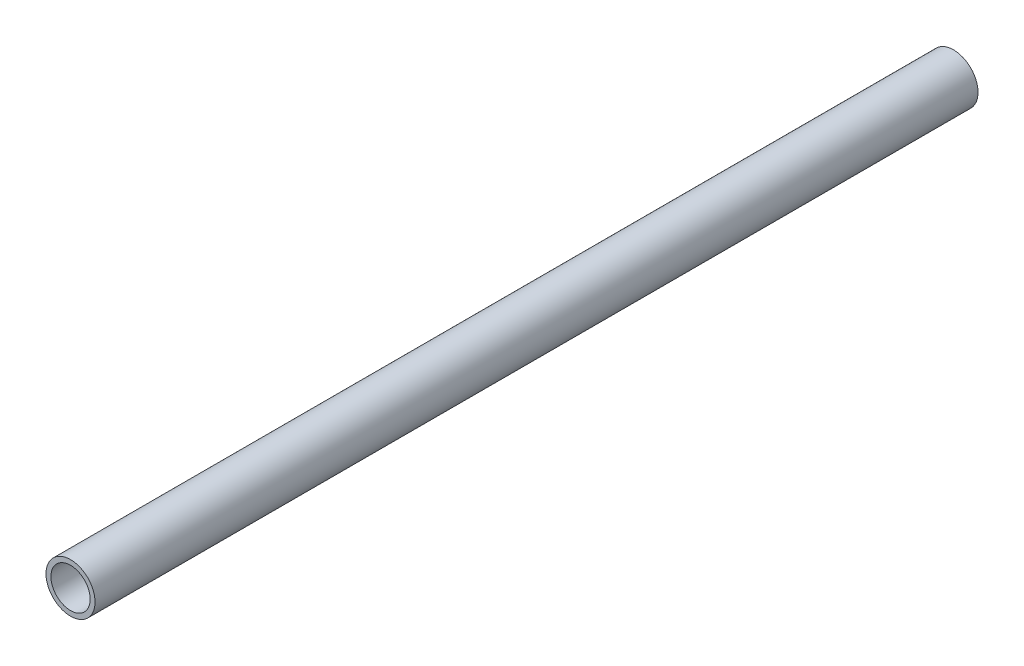
SolidWorks part; units mm, degrees
material "Thornel Mat VMA"
ref_plane "前视基准面" through (0, 0, 0) normal (0, 0, 1) x (1, 0, 0)
ref_plane "上视基准面" through (0, 0, 0) normal (0, 1, 0) x (1, 0, 0)
ref_plane "右视基准面" through (0, 0, 0) normal (1, 0, 0) x (0, 0, -1)
sketch "草图1" plane through (0, 0, 0) normal (0, 0, 1) x (1, 0, 0)
  circle A0 centre (0, 0) radius 4
  circle A1 centre (0, 0) radius 5
  dimension "D1" = 10
  dimension "D2" = 8
extrude "凸台-拉伸1" add sketch "草图1" along normal blind 180
